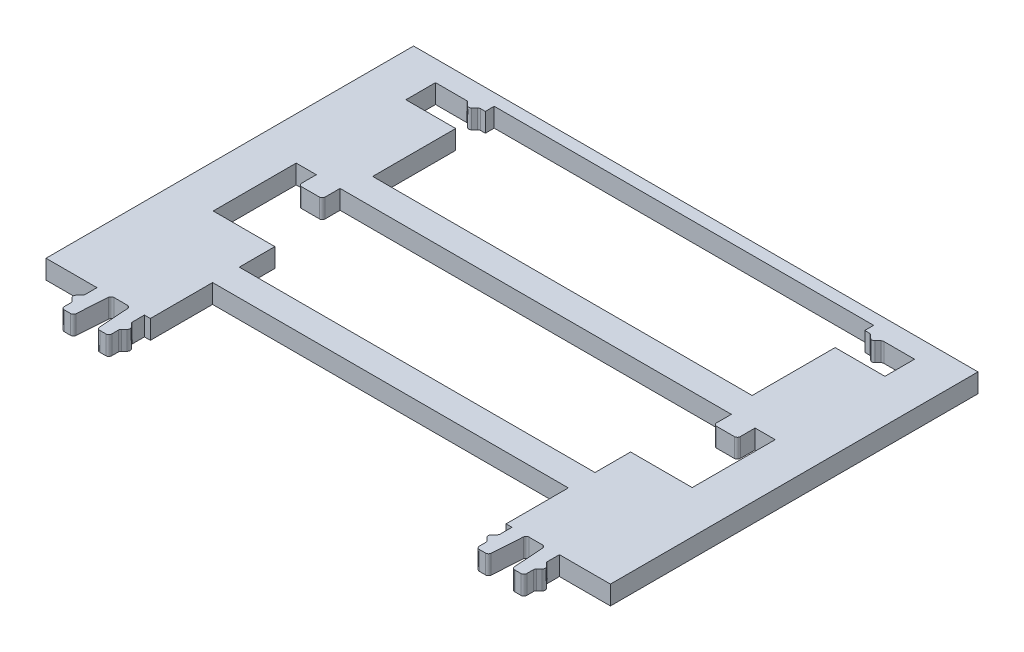
SolidWorks part; units mm, degrees
ref_plane "Front Plane" through (0, 0, 0) normal (0, 0, 1) x (1, 0, 0)
ref_plane "Top Plane" through (0, 0, 0) normal (0, 1, 0) x (1, 0, 0)
ref_plane "Right Plane" through (0, 0, 0) normal (1, 0, 0) x (0, 0, -1)
sketch "Sketch1" plane through (0, 0, 0) normal (0, 1, 0) x (1, 0, 0)
  line L0 (-68.9296, 0) -> (-64.6296, 0)
  line L1 (-60.1296, 0) -> (-60.1296, 5.25)
  line L2 (-61.6296, 17.5) -> (-61.6296, 16.25)
  line L3 (-65.3296, 10.5) -> (-65.3296, 17.5)
  line L4 (-65.3296, 17.5) -> (-63.6296, 17.5)
  line L5 (-64.6296, 0) -> (-64.6296, -0.9964)
  line L6 (-64.3796, -3) -> (-63.8635, -3)
  line L7 (-60.1296, 7.5) -> (-45.1296, 7.5)
  line L8 (-45.1296, 19.75) -> (-61.1296, 19.75)
  line L9 (-61.1296, 19.75) -> (-61.1296, 26.75)
  line L10 (-61.1296, 29.25) -> (-61.1296, 30)
  line L11 (-63.1957, 0) -> (-62.0635, 0)
  line L12 (-68.9296, 0) -> (-68.9296, 20)
  line L13 (-68.9296, 31) -> (-45.1296, 31)
  line L14 (-45.1296, 31) -> (-45.1296, 0) construction
  line L15 (-45.1296, 31) -> (-45.1296, 30)
  line L16 (-63.614, -2.7666) -> (-63.4451, -0.2334)
  line L17 (-61.3957, -3) -> (-60.8796, -3)
  line L18 (-61.814, -0.2334) -> (-61.6451, -2.7666)
  line L19 (-61.1296, 26.75) -> (-65.3296, 26.75)
  line L20 (-64.7028, -1.1732) -> (-64.9528, -1.4232)
  line L21 (-64.9528, -1.7768) -> (-64.7028, -2.0268)
  line L22 (-64.6296, -2.2036) -> (-64.6296, -2.75)
  line L23 (-60.6296, 0) -> (-60.6296, -0.9964)
  line L24 (-60.5564, -1.1732) -> (-60.3064, -1.4232)
  line L25 (-60.3064, -1.7768) -> (-60.5564, -2.0268)
  line L26 (-60.6296, -2.2036) -> (-60.6296, -2.75)
  line L27 (-65.3296, 10.5) -> (-60.1296, 10.5)
  line L28 (-61.8796, 16) -> (-63.3796, 16)
  line L29 (-63.6296, 16.25) -> (-63.6296, 17.5)
  line L30 (-45.1296, 19.75) -> (-45.1296, 17.5)
  line L31 (-45.1296, 5.25) -> (-60.1296, 5.25)
  line L32 (-60.6296, 0) -> (-60.1296, 0)
  line L33 (-60.1296, 7.5) -> (-60.1296, 10.5)
  line L34 (-61.6296, 17.5) -> (-45.1296, 17.5)
  line L36 (-65.3296, 26.75) -> (-65.3296, 29.25)
  line L37 (-65.3296, 29.25) -> (-62.7331, 29.25)
  line L38 (-61.1296, 30) -> (-45.1296, 30)
  line L39 (-62.5564, 29.1768) -> (-62.3064, 28.9268)
  line L40 (-61.9528, 28.9268) -> (-61.7028, 29.1768)
  line L41 (-61.526, 29.25) -> (-61.1296, 29.25)
  line L44 (-45.1296, 7.5) -> (-45.1296, 5.25)
  line L61 (-68.9296, 20) -> (-68.9296, 31)
  arc A1 (-61.526, 29.25) -> (-61.7028, 29.1768) centre (-61.526, 29) ccw
  arc A2 (-61.9528, 28.9268) -> (-62.3064, 28.9268) centre (-62.1296, 29.1036) cw
  arc A3 (-62.5564, 29.1768) -> (-62.7331, 29.25) centre (-62.7331, 29) ccw
  arc A4 (-60.6296, -0.9964) -> (-60.5564, -1.1732) centre (-60.3796, -0.9964) ccw
  arc A5 (-60.3064, -1.4232) -> (-60.3064, -1.7768) centre (-60.4831, -1.6) cw
  arc A6 (-60.5564, -2.0268) -> (-60.6296, -2.2036) centre (-60.3796, -2.2036) ccw
  arc A7 (-60.6296, -2.75) -> (-60.8796, -3) centre (-60.8796, -2.75) cw
  arc A8 (-61.3957, -3) -> (-61.6451, -2.7666) centre (-61.3957, -2.75) cw
  arc A9 (-61.814, -0.2334) -> (-62.0635, 0) centre (-62.0635, -0.25) ccw
  arc A10 (-63.1957, 0) -> (-63.4451, -0.2334) centre (-63.1957, -0.25) ccw
  arc A11 (-63.614, -2.7666) -> (-63.8635, -3) centre (-63.8635, -2.75) cw
  arc A12 (-64.3796, -3) -> (-64.6296, -2.75) centre (-64.3796, -2.75) cw
  arc A13 (-64.6296, -2.2036) -> (-64.7028, -2.0268) centre (-64.8796, -2.2036) ccw
  arc A14 (-64.9528, -1.7768) -> (-64.9528, -1.4232) centre (-64.776, -1.6) cw
  arc A15 (-64.7028, -1.1732) -> (-64.6296, -0.9964) centre (-64.8796, -0.9964) ccw
  arc A16 (-61.6296, 16.25) -> (-61.8796, 16) centre (-61.8796, 16.25) cw
  arc A17 (-63.3796, 16) -> (-63.6296, 16.25) centre (-63.3796, 16.25) cw
  point P25 (-61.6296, 29.25)
  point P30 (-62.1296, 28.75)
  point P47 (-62.6296, 29.25)
  point P54 (-60.6296, -1.1)
  point P57 (-60.1296, -1.6)
  point P62 (-60.6296, -3)
  point P66 (-61.6296, -3)
  point P74 (-61.8296, 0)
  point P77 (-63.4296, 0)
  point P80 (-63.6296, -3)
  point P83 (-64.6296, -3)
  point P86 (-64.6296, -2.1)
  point P89 (-65.1296, -1.6)
  point P92 (-64.6296, -1.1)
  point P96 (-61.6296, 16)
  point P99 (-63.6296, 16)
  dimension "D13" = 0.25
  dimension "D42" = 0.25
  dimension "D44" = 0.25
  dimension "D4" = 1.6
  dimension "D6" = 3
  dimension "D7" = 15
  dimension "D8" = 7
  dimension "D9" = 23.8
  dimension "D10" = 20.2
  dimension "D11" = 16
  dimension "D12" = 10.5
  dimension "D18" = 3
  dimension "D19" = 0.75
  dimension "D20" = 7
  dimension "D22" = 1
  dimension "D23" = 0.5
  dimension "D24" = 0.5
  dimension "D25" = 0.5
  dimension "D28" = 2.5
  dimension "D29" = 1.5
  dimension "D31" = 1.2
  dimension "D32" = 1
  dimension "D33" = 1
  dimension "D34" = 1.2
  dimension "D35" = 4
  dimension "D36" = 0.5
  dimension "D37" = 0.5
  dimension "D38" = 0.5
  dimension "D39" = 1.6
  dimension "D40" = 0.5
  dimension "D41" = 0.5
  dimension "D43" = 2
  dimension "D47" = 31
  dimension "D48" = 2.25
other "AlignGroup1"
extrude "Boss-Extrude1" add sketch "Sketch1" along normal blind 1.6
mirror "Mirror1" about plane through (-45.1296, 1.6, -31) normal (-1, 0, 0) of "Boss-Extrude1"
